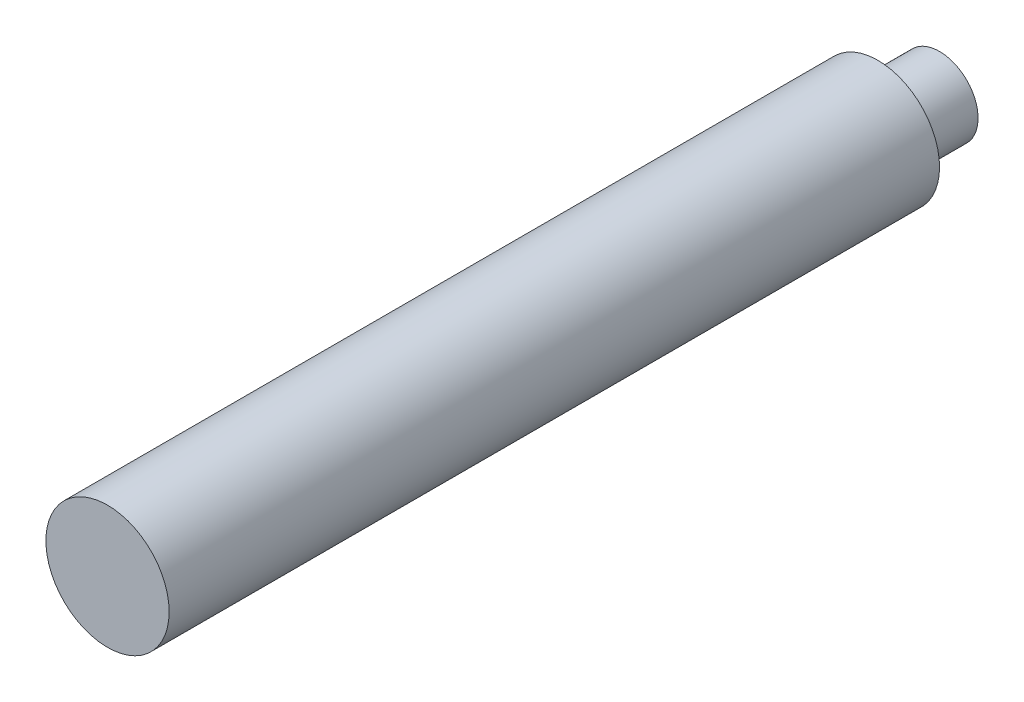
SolidWorks part; units mm, degrees
ref_plane "Front Plane" through (0, 0, 0) normal (0, 0, 1) x (1, 0, 0)
ref_plane "Top Plane" through (0, 0, 0) normal (0, 1, 0) x (1, 0, 0)
ref_plane "Right Plane" through (0, 0, 0) normal (1, 0, 0) x (0, 0, -1)
sketch "Sketch1" plane through (0, 0, 0) normal (0, 0, 1) x (1, 0, 0)
  circle A0 centre (0, 0) radius 5.08
  dimension "D1" = 10.16
extrude "Boss-Extrude1" add sketch "Sketch1" along normal blind 63.5
sketch "Sketch2" plane through (0, 0, 0) normal (0, 0, -1) x (-1, 0, 0)
  circle A0 centre (0, 0) radius 3.175
  dimension "D1" = 6.35
extrude "Boss-Extrude2" add sketch "Sketch2" along normal blind 5.08
